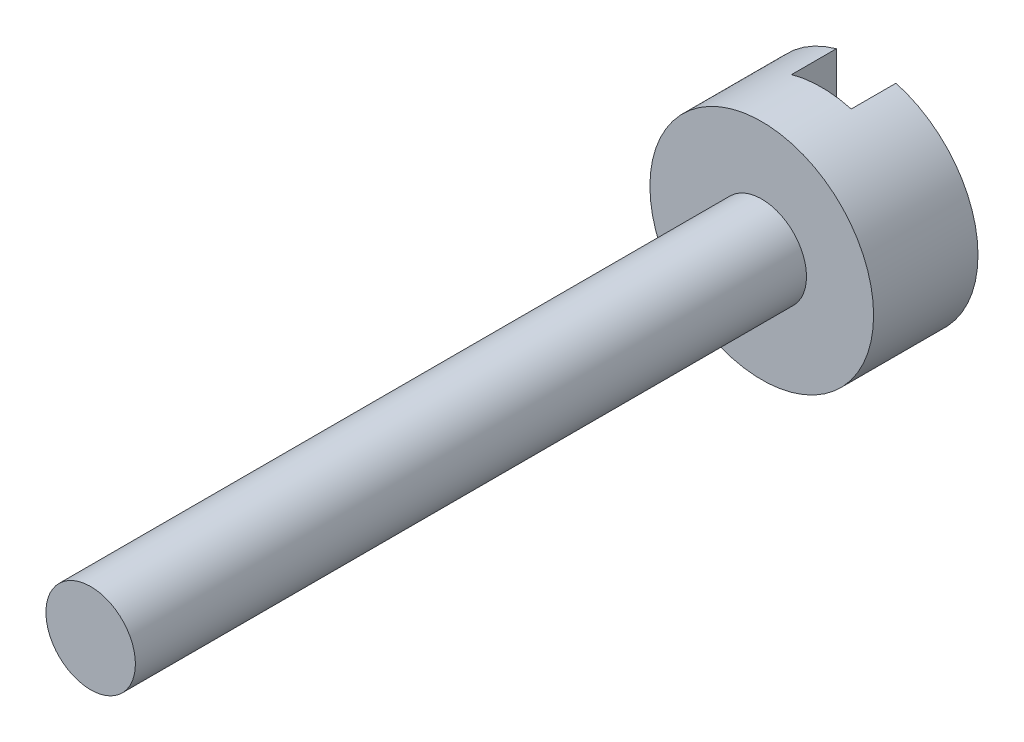
SolidWorks part; units mm, degrees
material "Plain Carbon Steel"
ref_plane "Front Plane" through (0, 0, 0) normal (0, 0, 1) x (1, 0, 0)
ref_plane "Top Plane" through (0, 0, 0) normal (0, 1, 0) x (1, 0, 0)
ref_plane "Right Plane" through (0, 0, 0) normal (1, 0, 0) x (0, 0, -1)
sketch "Sketch1" plane through (0, 0, 0) normal (0, 0, 1) x (1, 0, 0)
  circle A0 centre (0, 0) radius 0.75
  dimension "D1" = 1.5
extrude "Boss-Extrude1" add sketch "Sketch1" along normal blind 0.7
sketch "Sketch3" plane through (0, 0, 0.7) normal (0, 0, 1) x (1, 0, 0)
  circle A0 centre (0, 0) radius 0.3
  dimension "D1" = 0.6
extrude "Boss-Extrude2" add sketch "Sketch3" along normal blind 4.5
sketch "Sketch5" plane through (0, 0, 0) normal (0, 0, -1) x (-1, 0, 0)
  line L1 (-0.2, 1) -> (0.2, 1)
  line L2 (-0.2, 1) -> (-0.2, -1)
  line L3 (-0.2, -1) -> (0.2, -1)
  line L4 (0.2, 1) -> (0.2, -1)
  line L5 (-0.2, 1) -> (0.2, -1) construction
  line L6 (-0.2, -1) -> (0.2, 1) construction
  point P0 (0, 0)
  dimension "D1" = 0.4
  dimension "D2" = 2
extrude "Cut-Extrude1" cut sketch "Sketch5" against normal blind 0.3
